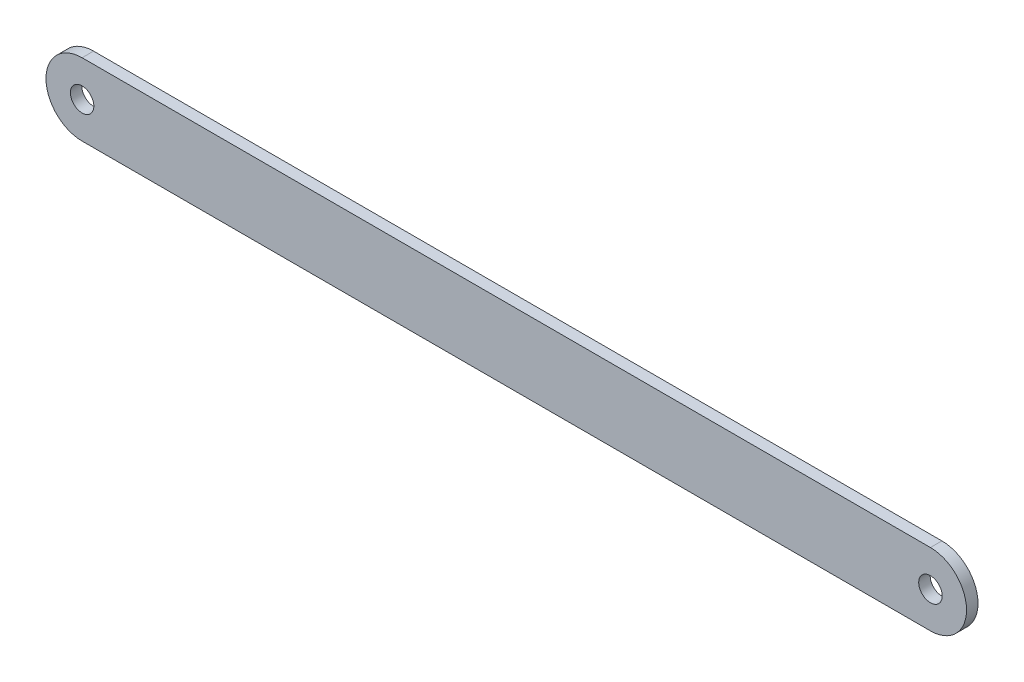
SolidWorks part; units mm, degrees
material "AISI 1020 Steel, Cold Rolled"
ref_plane "Front Plane" through (0, 0, 0) normal (0, 0, 1) x (1, 0, 0)
ref_plane "Top Plane" through (0, 0, 0) normal (0, 1, 0) x (1, 0, 0)
ref_plane "Right Plane" through (0, 0, 0) normal (1, 0, 0) x (0, 0, -1)
sketch "Sketch1" plane through (0, 0, 0) normal (0, 0, 1) x (1, 0, 0)
  line L0 (0, 0) -> (235, 0) construction
  line L1 (0, 10) -> (235, 10)
  line L2 (0, -10) -> (235, -10)
  arc A0 (0, 10) -> (0, -10) centre (0, 0) ccw
  arc A1 (235, -10) -> (235, 10) centre (235, 0) ccw
  circle A2 centre (0, 0) radius 3.25
  circle A3 centre (235, 0) radius 3.25
  point P3 (117.5, 0)
  dimension "D2" = 6.5
  dimension "D3" = 10
  dimension "D1" = 235
extrude "Boss-Extrude1" add sketch "Sketch1" along normal blind 3.175
